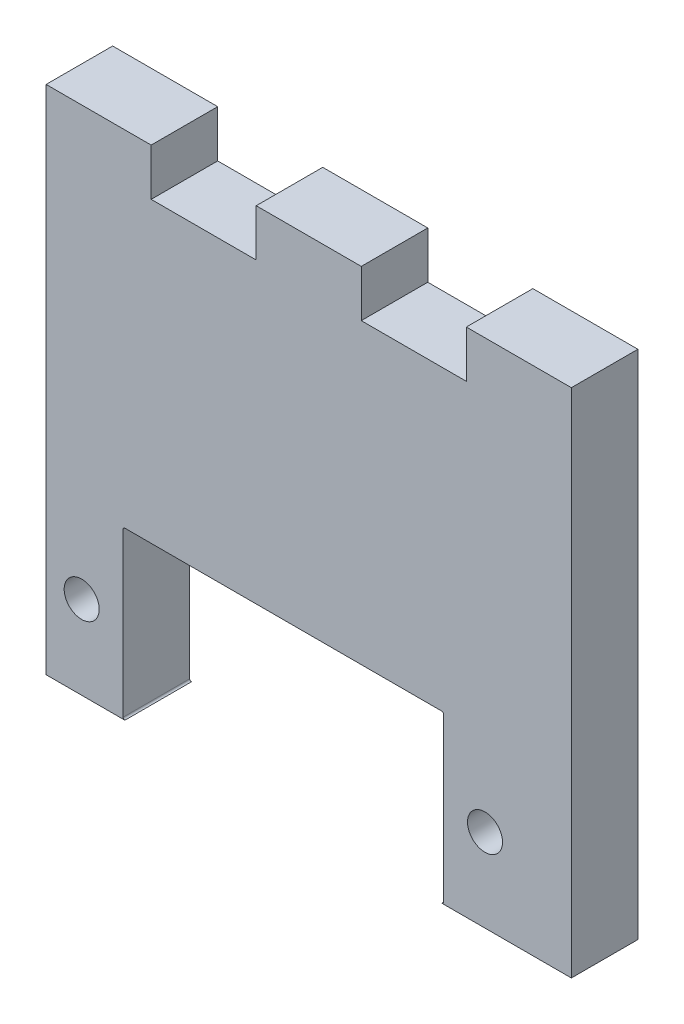
SolidWorks part; units mm, degrees
ref_plane "Front Plane" through (0, 0, 0) normal (0, 0, 1) x (1, 0, 0)
ref_plane "Top Plane" through (0, 0, 0) normal (0, 1, 0) x (1, 0, 0)
ref_plane "Right Plane" through (0, 0, 0) normal (1, 0, 0) x (0, 0, -1)
sketch "Sketch1" plane through (0, 0, 0) normal (0, 0, 1) x (1, 0, 0)
  line L1 (0, 0) -> (38.1, 0)
  line L2 (0, 0) -> (0, 37.084)
  line L3 (0, 37.084) -> (38.1, 37.084)
  line L4 (38.1, 0) -> (38.1, 37.084)
  dimension "D1" = 38.1
  dimension "D2" = 37.084
extrude "Boss-Extrude1" add sketch "Sketch1" along normal blind 4.826
sketch "Sketch3" plane through (0, 0, 4.826) normal (0, 0, 1) x (1, 0, 0)
  circle A2 centre (2.5805, 6.0325) radius 1.27
  circle A3 centre (31.8365, 6.0325) radius 1.27
extrude "Cut-Extrude2" cut sketch "Sketch3" against normal through all
sketch "Sketch4" plane through (0, 0, 0) normal (0, 0, -1) x (-1, 0, 0)
  line L0 (-28.702, 12.065) -> (-5.715, 12.065) construction
  line L1 (-28.829, 0.127) -> (-28.829, 11.938) construction
  line L2 (-5.588, 11.938) -> (-5.588, 0.127) construction
  line L3 (-5.715, 0) -> (-28.702, 0) construction
  line L4 (-28.702, 12.065) -> (-5.715, 12.065)
  line L5 (-28.829, 0.127) -> (-28.829, 11.938)
  line L6 (-5.588, 11.938) -> (-5.588, 0.127)
  line L7 (-5.715, 0) -> (-28.702, 0)
  arc A0 (-5.715, 0) -> (-5.588, 0.127) centre (-5.715, 0.127) ccw construction
  arc A1 (-28.829, 0.127) -> (-28.702, 0) centre (-28.702, 0.127) ccw construction
  arc A2 (-28.702, 12.065) -> (-28.829, 11.938) centre (-28.702, 11.938) ccw construction
  arc A3 (-5.588, 11.938) -> (-5.715, 12.065) centre (-5.715, 11.938) ccw construction
  arc A4 (-5.715, 0) -> (-5.588, 0.127) centre (-5.715, 0.127) ccw
  arc A5 (-28.829, 0.127) -> (-28.702, 0) centre (-28.702, 0.127) ccw
  arc A6 (-28.702, 12.065) -> (-28.829, 11.938) centre (-28.702, 11.938) ccw
  arc A7 (-5.588, 11.938) -> (-5.715, 12.065) centre (-5.715, 11.938) ccw
extrude "Cut-Extrude3" cut sketch "Sketch4" against normal through all
sketch "Sketch5" plane through (0, 0, 4.826) normal (0, 0, 1) x (1, 0, 0)
  line L0 (38.1, 37.084) -> (0, 37.084) construction
  line L1 (7.62, 37.084) -> (15.24, 37.084)
  line L2 (7.62, 37.084) -> (7.62, 33.6741)
  line L3 (7.62, 33.6741) -> (15.24, 33.6741)
  line L4 (15.24, 37.084) -> (15.24, 33.6741)
  line L5 (0, 33.6741) -> (7.62, 33.6741) construction
  line L6 (22.86, 37.084) -> (30.48, 37.084)
  line L7 (22.86, 37.084) -> (22.86, 33.6741)
  line L8 (22.86, 33.6741) -> (30.48, 33.6741)
  line L9 (30.48, 37.084) -> (30.48, 33.6741)
  line L10 (0, 37.084) -> (0, 0) construction
  line L11 (15.24, 33.6741) -> (22.86, 33.6741) construction
  line L12 (30.48, 33.6741) -> (38.1, 33.6741) construction
  line L13 (38.1, 0) -> (38.1, 37.084) construction
extrude "Cut-Extrude4" cut sketch "Sketch5" against normal through all
equation "\"MDF\"= 0.19in"
equation "\"PVCID\"= 2.067in"
equation "\"PVCOD\"= 2.375in"
equation "\"GenDiameter\"= 60mm"
equation "\"GenCutDiameter\"= 1.8in"
equation "\"GenCutDistance\"= 1"
equation "\"TowerHeight\"= 6in"
equation "\"TowerFrontBase\"= 3in"
equation "\"FunnelHeight\"= 1in"
equation "\"FunnelAngle\"= 20"
equation "\"TowerSideBase\"= 3in"
equation "\"TowerPanelLength\"= 2in"
equation "\"TowerPanelLeeway\"= 0.5in"
equation "\"BaseLength\"= 9in"
equation "\"BaseWidth\"= 10in"
equation "\"WheelHoleLength\"= 3.25in"
equation "\"WheelHoleWidth\"= 26mm"
equation "\"WheelHoleFromBack\"= 1.5in"
equation "\"DropLength\"= 1in"
equation "\"DropWidth\"= 8.5in"
equation "\"BumperWidth\"= 2in"
equation "\"SmallHexDiameter\"= 0.185in"
equation "\"SmallHexHeight\"= 0.701in"
equation "\"ScrewSize\"= 0.106in"
equation "\"BigHexDiameter\"= 0.251in"
equation "\"BigHexHeight\"= 0.374in"
equation "\"PCBThickness\"= 0.066in"
equation "\"ConnectorHeight\"= 0.517in"
equation "\"BoardHeight\"= 0.583in"
equation "\"UnoStackHeight\"= 1.351in"
equation "\"UnoStackWidth\"= 3.053in"
equation "\"UnoStackLength\"= 3.152in"
equation "\"HBridgeWidth\"= 1.797in"
equation "\"HBridgeLength\"= 2.236in"
equation "\"DSWidth\"= 1.820in"
equation "\"DSLength\"= 1.833in"
equation "\"StepperWidth\"= 1.799in"
equation "\"StepperLength\"= 2.248in"
equation "\"ULNWidth\"= 1.304in"
equation "\"ULNLength\"= 1.545in"
equation "\"VSwitchHeight\"= 0.392in"
equation "\"VSwitchWidth\"= 0.637in"
equation "\"VSwitchLength\"= 1.097in"
equation "\"SkateWheelDiameter\"= 80mm"
equation "\"SkateWheelThickness\"= 24mm"
equation "\"BaseDistance\"= 3in"
equation "\"DummyVar\"= 2in"
equation "\"D1@Boss-Extrude1\"=\"MDF\""
equation "\"D2@Sketch1\"=\"MDF\"+1.27in"
